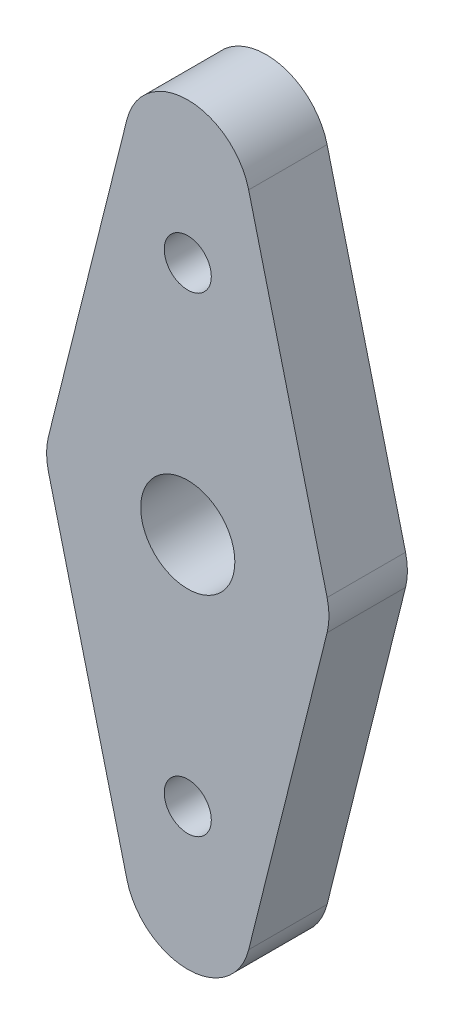
SolidWorks part; units mm, degrees
ref_plane "前基準面" through (0, 0, 0) normal (0, 0, 1) x (1, 0, 0)
ref_plane "上基準面" through (0, 0, 0) normal (0, 1, 0) x (1, 0, 0)
ref_plane "右基準面" through (0, 0, 0) normal (1, 0, 0) x (0, 0, -1)
sketch "草圖1" plane through (0, 0, 0) normal (0, 0, 1) x (1, 0, 0)
  line L0 (0, 20) -> (0, -20) construction
  line L1 (0, 20) -> (-5, 0) construction
  line L2 (-5, 0) -> (0, -20) construction
  line L3 (0, -20) -> (5, 0) construction
  line L4 (5, 0) -> (0, 20) construction
  line L5 (-5, 0) -> (5, 0) construction
  line L6 (-3.8806, 20.9701) -> (-8.8806, 0.9701)
  line L7 (-8.8806, -0.9701) -> (-3.8806, -20.9701)
  line L8 (3.8806, -20.9701) -> (8.8806, -0.9701)
  line L9 (8.8806, 0.9701) -> (3.8806, 20.9701)
  line L10 (-8.8806, 0.9701) -> (8.8806, -0.9701) construction
  line L11 (8.8806, 0.9701) -> (-8.8806, -0.9701) construction
  arc A0 (-8.8806, 0.9701) -> (-8.8806, -0.9701) centre (-5, 0) ccw
  arc A1 (-3.8806, -20.9701) -> (3.8806, -20.9701) centre (0, -20) ccw
  arc A2 (8.8806, -0.9701) -> (8.8806, 0.9701) centre (5, 0) ccw
  arc A3 (3.8806, 20.9701) -> (-3.8806, 20.9701) centre (0, 20) ccw
  dimension "D1" = 10
  dimension "D2" = 40
  dimension "D3" = 4
extrude "伸長1" add sketch "草圖1" along normal blind 5
sketch "草圖2" plane through (0, 0, 5) normal (0, 0, 1) x (1, 0, 0)
  circle A0 centre (0, 0) radius 3
  dimension "D1" = 6
extrude "伸長2" cut sketch "草圖2" against normal through all
sketch "草圖3" plane through (0, 0, 5) normal (0, 0, 1) x (1, 0, 0)
  line L0 (0, 15) -> (0, -15) construction
  circle A0 centre (0, 15) radius 1.5
  circle A1 centre (0, -15) radius 1.5
  dimension "D1" = 3
  dimension "D2" = 3
  dimension "D3" = 30
extrude "伸長3" cut sketch "草圖3" against normal blind 100
